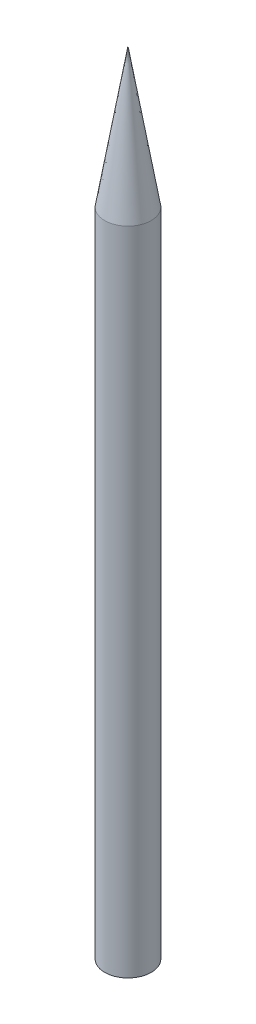
SolidWorks part; units mm, degrees
ref_plane "Front Plane" through (0, 0, 0) normal (0, 0, 1) x (1, 0, 0)
ref_plane "Top Plane" through (0, 0, 0) normal (0, 1, 0) x (1, 0, 0)
ref_plane "Right Plane" through (0, 0, 0) normal (1, 0, 0) x (0, 0, -1)
sketch "Sketch1" plane through (0, 0, 0) normal (0, 1, 0) x (1, 0, 0)
  circle A0 centre (0, 0) radius 3.175
  dimension "D1" = 6.35
extrude "Boss-Extrude1" add sketch "Sketch1" along normal blind 88.9
sketch "Sketch3" plane through (0, 0, 0) normal (0, 0, 1) x (1, 0, 0)
  line L0 (0, 0) -> (0, 119.8513) construction
  line L1 (-3.175, 88.9) -> (0, 107.95)
  line L2 (3.175, 88.9) -> (-3.175, 88.9) construction
  line L3 (-3.175, 88.9) -> (0, 88.9)
  line L4 (0, 88.9) -> (0, 107.95)
  dimension "D1" = 19.05
revolve "Revolve1" add sketch "Sketch3" angle 360 about L4
